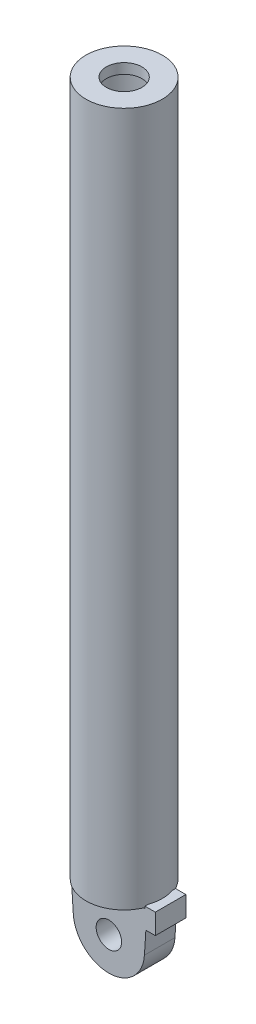
SolidWorks part; units mm, degrees
material "Plain Carbon Steel"
ref_plane "Front Plane" through (0, 0, 0) normal (0, 0, 1) x (1, 0, 0)
ref_plane "Top Plane" through (0, 0, 0) normal (0, 1, 0) x (1, 0, 0)
ref_plane "Right Plane" through (0, 0, 0) normal (1, 0, 0) x (0, 0, -1)
sketch "Sketch1" plane through (0, 0, 0) normal (0, 0, 1) x (1, 0, 0)
  line L0 (37.5, 40) -> (37.5, 722) construction
  line L1 (37.6286, 42) -> (35.5, 42)
  line L2 (37.6286, 42) -> (45.6286, 42)
  line L3 (45.6286, 42) -> (45.6286, 22)
  line L4 (45.6286, 22) -> (36.3425, 22)
  line L5 (37.5, 40) -> (-37.5, 40) construction
  line L6 (37.5, 722) -> (-37.5, 722) construction
  line L7 (-37.5, 40) -> (-37.5, 722) construction
  line L8 (37.5, 40) -> (34.9279, 0) construction
  line L9 (-37.5, 40) -> (-34.9279, 0)
  line L10 (0, 40) -> (0, -105.1053) construction
  line L11 (34.9279, 0) -> (-34.9279, 0) construction
  line L12 (0, 722) -> (0, 40) construction
  line L13 (37.5, 172) -> (-37.5, 172) construction
  line L14 (36.3425, 22) -> (34.9279, 0)
  line L15 (-37.5, 40) -> (35.5, 40)
  line L16 (45.6286, 32) -> (39.38, 32) construction
  line L17 (35.5, 42) -> (35.5, 40)
  arc A0 (-34.9279, 0) -> (34.9279, 0) centre (0, 2.246) ccw
  circle A1 centre (0, 0) radius 12.5
  dimension "D2" = 35
  dimension "D3" = 25
  dimension "D1" = 75
  dimension "D4" = 40
  dimension "D5" = 722
  dimension "D6" = 550
  dimension "D7" = 20
  dimension "D8" = 32
  dimension "D9" = 2
  dimension "D11" = 8
extrude "Boss-Extrude1" add sketch "Sketch1" along normal mid plane 30
sketch "Sketch2" plane through (0, 0, 0) normal (0, 0, 1) x (1, 0, 0)
  line L0 (37.5, 40) -> (37.5, 722) construction
  line L1 (37.5, 40) -> (-37.5, 40) construction
  line L2 (37.5, 722) -> (-37.5, 722) construction
  line L3 (-37.5, 40) -> (-37.5, 722) construction
  line L4 (37.5, 40) -> (34.9279, 0) construction
  line L5 (-37.5, 40) -> (-34.9279, 0) construction
  line L6 (0, 40) -> (0, -109.9514) construction
  line L7 (34.9279, 0) -> (-34.9279, 0) construction
  line L8 (0, 722) -> (0, 40) construction
  line L9 (37.5, 172) -> (-37.5, 172) construction
  line L10 (-37.5, 722) -> (-17.5, 722)
  line L11 (-17.5, 722) -> (-17.5, 712)
  line L12 (-17.5, 712) -> (-32.5, 712)
  line L13 (-32.5, 712) -> (-32.5, 172)
  line L14 (-32.5, 172) -> (0, 172)
  line L15 (0, 172) -> (0, 40)
  line L16 (0, 40) -> (-37.5, 40)
  line L17 (-37.5, 40) -> (-37.5, 722)
  arc A0 (-34.9279, 0) -> (34.9279, 0) centre (0, 2.246) ccw construction
  circle A1 centre (0, 0) radius 12.5 construction
  dimension "D2" = 35
  dimension "D3" = 25
  dimension "D1" = 75
  dimension "D4" = 40
  dimension "D5" = 722
  dimension "D6" = 550
  dimension "D7" = 5
  dimension "D8" = 17.5
  dimension "D10" = 10
revolve "Revolve1" add sketch "Sketch2" angle 360 about L8
